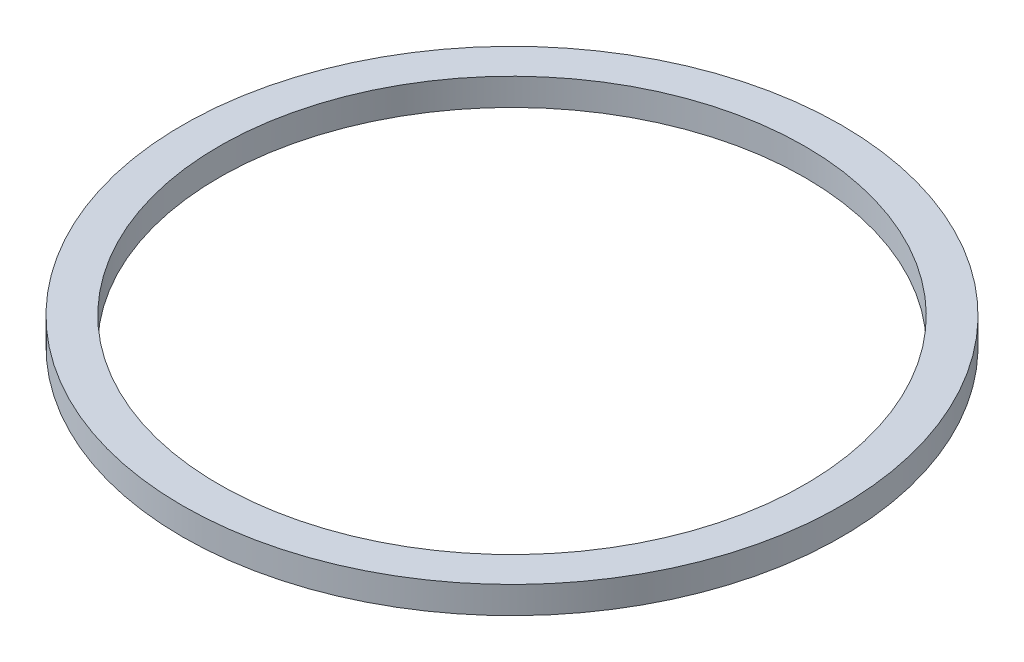
SolidWorks part; units mm, degrees
material "Hexcel AS4C (3000 Filaments)"
ref_plane "Front Plane" through (0, 0, 0) normal (0, 0, 1) x (1, 0, 0)
ref_plane "Top Plane" through (0, 0, 0) normal (0, 1, 0) x (1, 0, 0)
ref_plane "Right Plane" through (0, 0, 0) normal (1, 0, 0) x (0, 0, -1)
sketch "Sketch1" plane through (0, 0, 0) normal (0, 0, 1) x (1, 0, 0)
  line L0 (-60, 12.9625) -> (-60, 18.5) construction
  line L1 (-60, 12.9625) -> (-60, 18.5)
  line L2 (-67.5, 12.9625) -> (-67.5, 18.5) construction
  line L3 (-67.5, 12.9625) -> (-67.5, 18.5)
  line L4 (-60, 18.5) -> (-67.5, 18.5)
  line L5 (-60, 12.9625) -> (-67.5, 12.9625)
  line L6 (0, -200069.0475) -> (0, 200086.9028) construction
  line L7 (0, -200069.0475) -> (0, 200086.9028) construction
revolve "Revolve1" add sketch "Sketch1" angle 360 about L7
